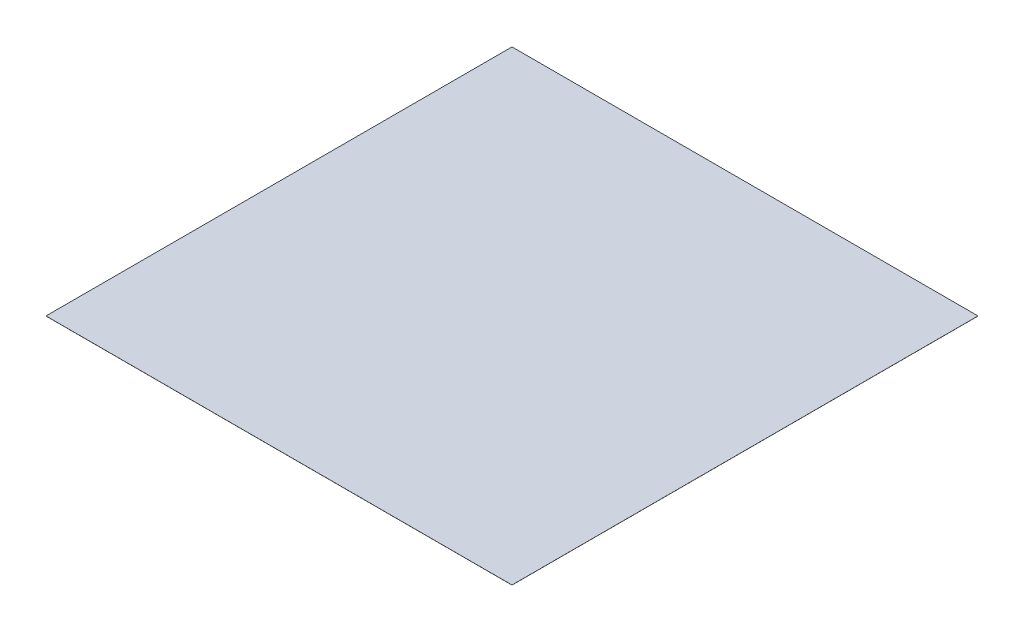
SolidWorks part; units mm, degrees
ref_plane "Front Plane" through (0, 0, 0) normal (0, 0, 1) x (1, 0, 0)
ref_plane "Top Plane" through (0, 0, 0) normal (0, 1, 0) x (1, 0, 0)
ref_plane "Right Plane" through (0, 0, 0) normal (1, 0, 0) x (0, 0, -1)
sketch "Sketch1" plane through (0, 0, 0) normal (0, 1, 0) x (1, 0, 0)
  line L1 (0, 0) -> (12700, 0)
  line L2 (0, 0) -> (0, 12700)
  line L3 (0, 12700) -> (12700, 12700)
  line L4 (12700, 0) -> (12700, 12700)
  dimension "D1" = 12700
  dimension "D2" = 12700
extrude "Boss-Extrude1" add sketch "Sketch1" along normal blind 2.54
